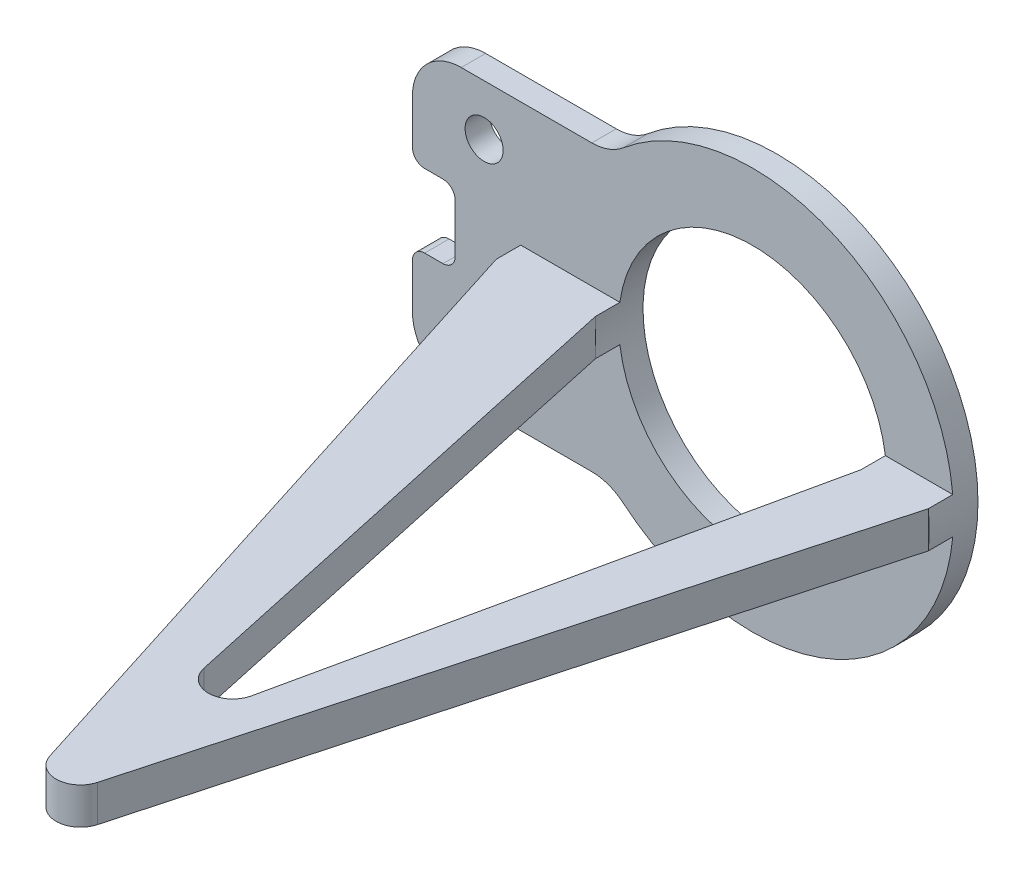
SolidWorks part; units mm, degrees
ref_plane "前视基准面" through (0, 0, 0) normal (0, 0, 1) x (1, 0, 0)
ref_plane "上视基准面" through (0, 0, 0) normal (0, 1, 0) x (1, 0, 0)
ref_plane "右视基准面" through (0, 0, 0) normal (1, 0, 0) x (0, 0, -1)
other "Configuration Table"
sketch "草图1" plane through (0, 0, 0) normal (0, 0, 1) x (1, 0, 0)
  line L10 (-13.1733, 11.6673) -> (-23.8733, 11.6673)
  line L19 (-27.8733, 7.6673) -> (-27.8733, -7.6673)
  line L25 (-23.8733, -11.6673) -> (-13.1733, -11.6673)
  arc A37 (-10.599, 12.6057) -> (-10.599, -12.6057) centre (0, 0) cw
  arc A46 (-10.599, -12.6057) -> (-13.1733, -11.6673) centre (-13.1733, -15.6673) ccw
  arc A47 (-10.599, 12.6057) -> (-13.1733, 11.6673) centre (-13.1733, 15.6673) cw
  circle A54 centre (-22, 7.5) radius 1.56
  circle A55 centre (-22, -7.5) radius 1.56
  circle A56 centre (0, 0) radius 10.981
  arc A60 (-23.8733, 11.6673) -> (-27.8733, 7.6673) centre (-23.8733, 7.6673) ccw
  arc A61 (-27.8733, -7.6673) -> (-23.8733, -11.6673) centre (-23.8733, -7.6673) ccw
  point P21 (0, 0)
  point P74 (-27.8733, 0)
  point P88 (-11.624, -11.6673)
  dimension "D1" = 4
  dimension "D8" = 4
  dimension "D9" = 4
  dimension "D2" = 4
extrude "凸台-拉伸1" add sketch "草图1" along normal blind 2
sketch "草图2" plane through (0, 0, 2) normal (0, 0, 1) x (1, 0, 0)
  line L1 (-19, 1.5) -> (-10.8781, 1.5)
  line L2 (1.1, 0) -> (-1.1, 0) construction
  line L9 (-27.8733, 0) -> (0, 0) construction
  line L10 (-27.8733, 7.6673) -> (-27.8733, -7.6673) construction
  line L11 (-19, -1.5) -> (-10.8781, -1.5)
  line L12 (-19, 1.5) -> (-19, -1.5)
  line L13 (10.8781, 1.5) -> (16.401, 1.5)
  line L14 (10.8781, -1.5) -> (16.401, -1.5)
  circle A1 centre (0, 0) radius 10.981 construction
  arc A2 (-10.8781, 1.5) -> (-10.8781, -1.5) centre (0, 0) ccw
  arc A3 (-10.599, -12.6057) -> (-10.599, 12.6057) centre (0, 0) ccw construction
  arc A4 (16.401, 1.5) -> (16.401, -1.5) centre (0, 0) cw
  arc A5 (10.8781, 1.5) -> (10.8781, -1.5) centre (0, 0) cw
extrude "凸台-拉伸3" add sketch "草图2" along normal blind 2
sketch "草图3" plane through (0, 1.5, 0) normal (0, 1, 0) x (1, 0, 0)
  line L0 (0, 0) -> (0, -64) construction
  line L1 (-10.8781, -4) -> (-1.9543, -45.0174)
  line L2 (10.8781, -4) -> (1.9543, -45.0174)
  line L3 (-19, -4) -> (-2.0475, -57.5341)
  line L4 (1.7884, -57.4576) -> (16.401, -4)
  line L5 (16.401, -4) -> (10.8781, -4)
  line L6 (-19, -4) -> (-10.8781, -4)
  arc A0 (-1.9543, -45.0174) -> (1.9543, -45.0174) centre (0, -44.5922) ccw
  arc A1 (-2.0475, -57.5341) -> (1.7884, -57.4576) centre (-0.1409, -56.9303) ccw
  point P15 (0, -54)
  dimension "D1" = 2
  dimension "D2" = 2
extrude "凸台-拉伸4" add sketch "草图3" against normal blind 3
sketch "草图4" plane through (0, 0, 0) normal (0, 0, -1) x (-1, 0, 0)
  line L0 (27.8733, -3) -> (27.8733, 3)
  line L1 (27.8733, 7.6673) -> (27.8733, -7.6673) construction
  line L2 (24.3885, 0) -> (-24.3885, 0) construction
  line L3 (27.8733, 3) -> (24.3733, 3)
  line L4 (24.3733, 3) -> (24.3733, -3)
  line L5 (24.3733, -3) -> (27.8733, -3)
  point P7 (27.8733, 0)
extrude "切除-拉伸1" cut sketch "草图4" against normal blind 10
fillet "圆角1" radius 1 1 edges at (-27.8733, 3, 1)
fillet "圆角2" radius 1 3 edges at (-24.3733, -3, 1) (-27.8733, -3, 1) (-24.3733, 3, 1)
